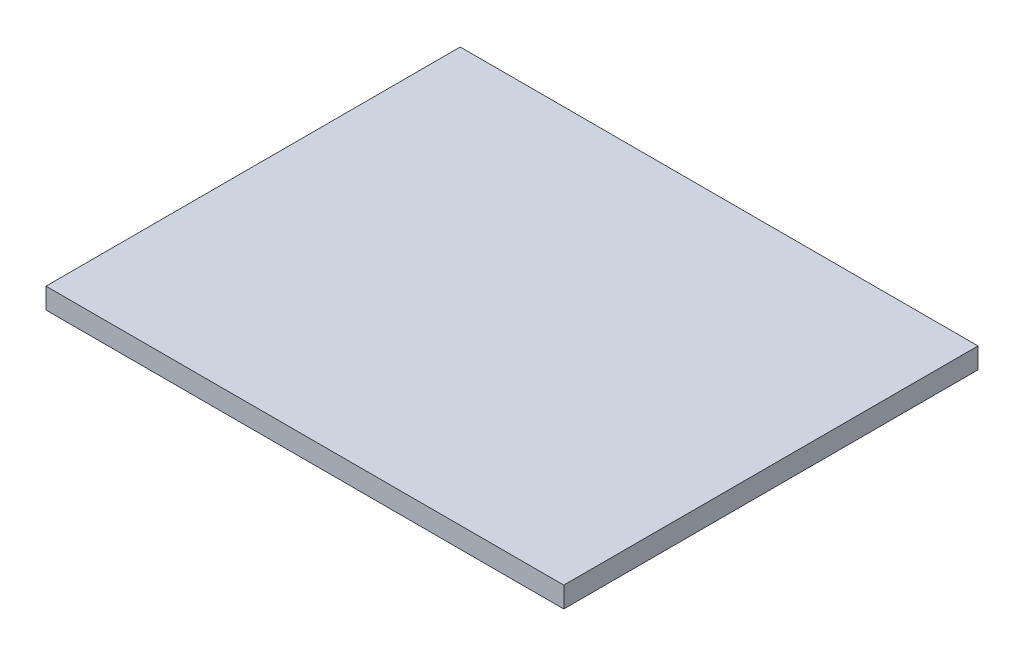
SolidWorks part; units mm, degrees
ref_plane "Front Plane" through (0, 0, 0) normal (0, 0, 1) x (1, 0, 0)
ref_plane "Top Plane" through (0, 0, 0) normal (0, 1, 0) x (1, 0, 0)
ref_plane "Right Plane" through (0, 0, 0) normal (1, 0, 0) x (0, 0, -1)
sketch "Sketch1" plane through (0, 0, 0) normal (0, 1, 0) x (1, 0, 0)
  line L1 (-250, 200) -> (250, 200)
  line L2 (-250, 200) -> (-250, -200)
  line L3 (-250, -200) -> (250, -200)
  line L4 (250, 200) -> (250, -200)
  line L5 (-250, 200) -> (250, -200) construction
  line L6 (-250, -200) -> (250, 200) construction
  point P0 (0, 0)
  dimension "D1" = 500
  dimension "D2" = 400
extrude "Boss-Extrude1" add sketch "Sketch1" along normal blind 20
